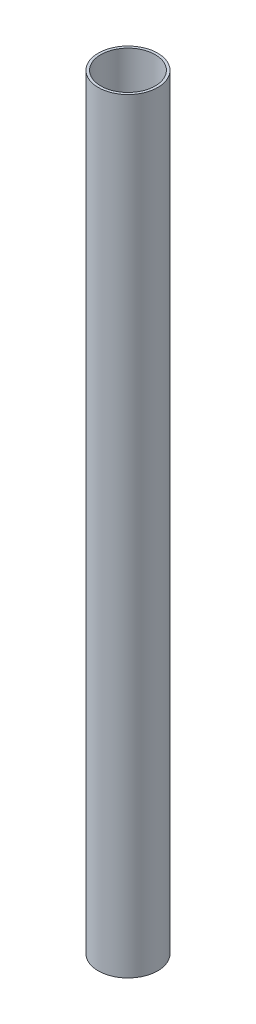
SolidWorks part; units mm, degrees
ref_plane "Alzado" through (0, 0, 0) normal (0, 0, 1) x (1, 0, 0)
ref_plane "Planta" through (0, 0, 0) normal (0, 1, 0) x (1, 0, 0)
ref_plane "Vista lateral" through (0, 0, 0) normal (1, 0, 0) x (0, 0, -1)
sketch "Croquis1" plane through (0, 0, 0) normal (0, 1, 0) x (1, 0, 0)
  circle A0 centre (0, 0) radius 17.5
  circle A1 centre (0, 0) radius 16
  dimension "D1" = 35
  dimension "D2" = 32
extrude "Saliente-Extruir1" add sketch "Croquis1" along normal blind 450
